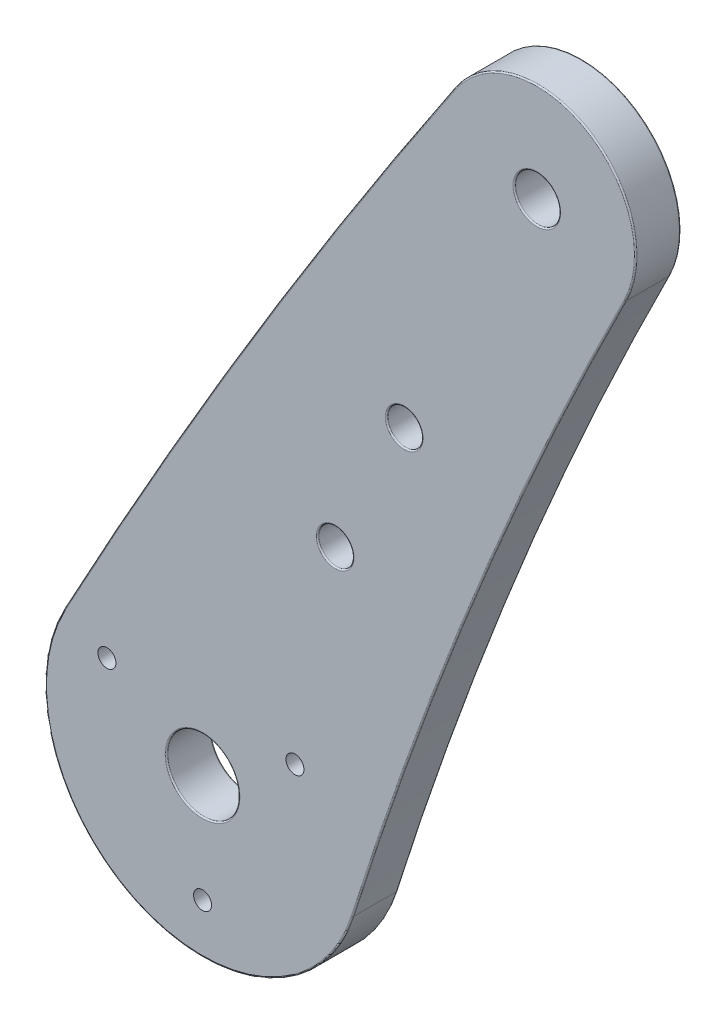
SolidWorks part; units mm, degrees
material "Cast Alloy Steel"
ref_plane "Front Plane" through (0, 0, 0) normal (0, 0, 1) x (1, 0, 0)
ref_plane "Top Plane" through (0, 0, 0) normal (0, 1, 0) x (1, 0, 0)
ref_plane "Right Plane" through (0, 0, 0) normal (1, 0, 0) x (0, 0, -1)
sketch "Sketch1" plane through (0, 0, 0) normal (0, 0, 1) x (1, 0, 0)
  line L0 (-20.22, 57.58) -> (16.9381, 131.648) construction
  line L1 (-20.22, 57.58) -> (16.9381, 131.648) construction
  circle A0 centre (16.9381, 131.648) radius 11 construction
  circle A1 centre (16.9381, 131.648) radius 11 construction
  circle A2 centre (-20.22, 57.58) radius 17.5 construction
  circle A3 centre (-20.22, 57.58) radius 17.5 construction
  circle A4 centre (-20.22, 57.58) radius 4
  circle A5 centre (16.9381, 131.648) radius 2.5
  arc A8 (7.8153, 137.794) -> (-35.628, 65.8772) centre (712.7617, -337.1277) ccw
  arc A9 (26.7596, 126.6944) -> (-3.5346, 52.303) centre (473.1916, -98.4689) ccw
  arc A10 (16.9381, 131.648) -> (-20.22, 57.58) centre (667.7057, -241.1811) ccw construction
  arc A11 (7.8153, 137.794) -> (26.7596, 126.6944) centre (16.9381, 131.648) cw
  arc A12 (-35.628, 65.8772) -> (-3.5346, 52.303) centre (-20.22, 57.58) ccw
  point P17 (2.2006, 102.2714)
  point P18 (-5.4825, 86.9566)
  dimension "D1" = 5
  dimension "D2" = 8
  dimension "D3" = 850
  dimension "D4" = 500
  dimension "D5" = 750
  dimension "D6" = 50
  dimension "D7" = 50
extrude "Boss-Extrude1" add sketch "Sketch1" along normal blind 5
hole_wizard "M3.5 Clearance Hole1" positions "Sketch2" profile "Sketch3" hole size "M3.5" standard "ISO" end condition through all
sketch "Sketch2" plane through (0, 0, 0) normal (0, 0, -1) x (-1, 0, 0)
  point P0 (-2.2006, 102.2714)
  point P3 (5.4825, 86.9566)
sketch "Sketch3" plane through (2.2006, 102.2714, 0) normal (1, 0, 0) x (0, 1, 0)
  line L0 (0, 0) -> (0, 5)
  line L1 (0, 5) -> (1.95, 5)
  line L2 (1.95, 5) -> (1.95, 0)
  line L5 (1.95, 0) -> (0, 0)
  line L11 (0, -6.35) -> (0, 107.95) construction
  dimension "Thru Hole Dia." = 3.9
  dimension "Thru Hole Depth" = 5
fillet "Fillet1" radius 0.15 16 edges at (0.2506, 102.2714, 0) (0.2506, 102.2714, 5) (-7.4325, 86.9566, 0) (-7.4325, 86.9566, 5) (19.4381, 131.648, 0) (19.4381, 131.648, 5) (-16.22, 57.58, 0) (22.4989, 141.1389, 0) (-14.7955, 102.3727, 0) (-27.0371, 41.4624, 0) (10.1163, 90.108, 0) (22.4989, 141.1389, 5) (-14.7955, 102.3727, 5) (-27.0371, 41.4624, 5) (10.1163, 90.108, 5) (-16.22, 57.58, 5)
sketch "Sketch4" plane through (0, 0, 5) normal (0, 0, 1) x (1, 0, 0)
  circle A2 centre (-20.22, 45.58) radius 1
  circle A3 centre (-20.22, 57.58) radius 4 construction
  circle A4 centre (-20.22, 57.58) radius 4.15 construction
  circle A5 centre (-30.8485, 63.58) radius 1
  circle A6 centre (-9.9458, 63.7846) radius 1
  point P15 (-20.3381, 57.6482)
  dimension "D1" = 2
  dimension "D2" = 12
  dimension "D3" = 0
  dimension "D4" = 3
  dimension "D5" = 6.2682
  dimension "D6" = 16.6605
extrude "Cut-Extrude1" cut sketch "Sketch4" against normal blind 10
